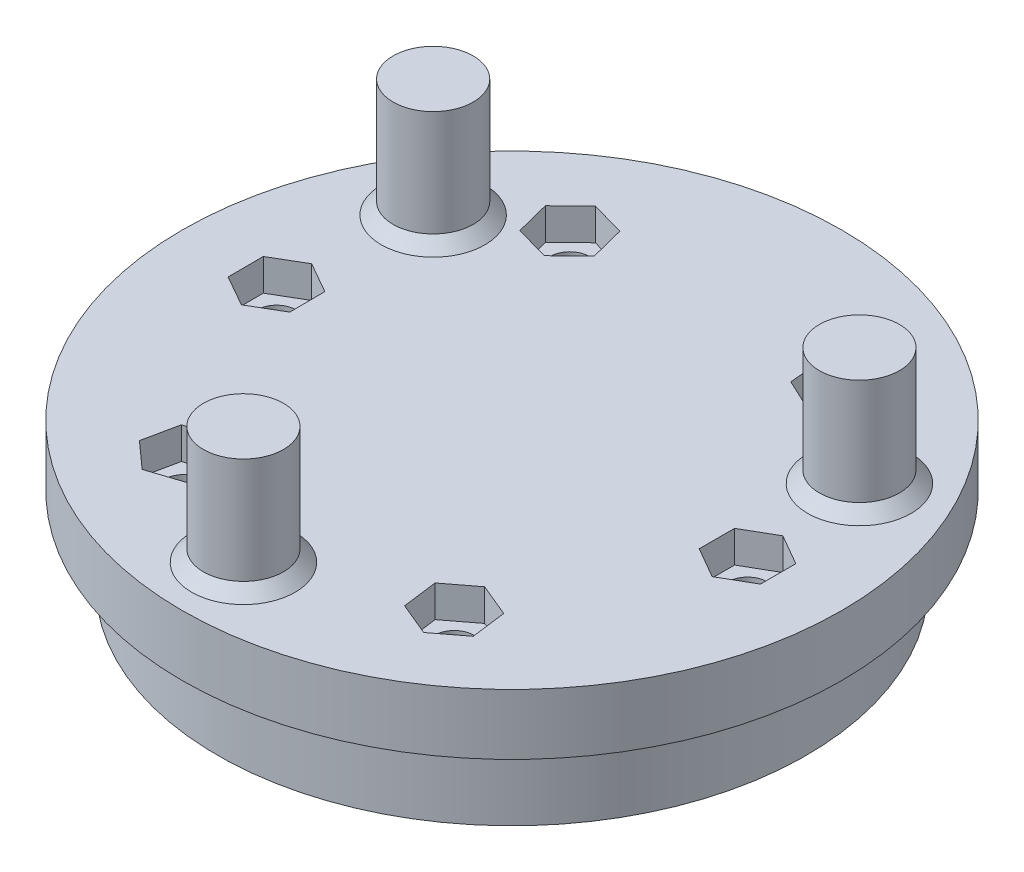
SolidWorks part; units mm, degrees
ref_plane "Front Plane" through (0, 0, 0) normal (0, 0, 1) x (1, 0, 0)
ref_plane "Top Plane" through (0, 0, 0) normal (0, 1, 0) x (1, 0, 0)
ref_plane "Right Plane" through (0, 0, 0) normal (1, 0, 0) x (0, 0, -1)
sketch "Sketch3" plane through (0, 0, 0) normal (0, 1, 0) x (1, 0, 0)
  circle A0 centre (0, 0) radius 28
  dimension "D1" = 56
extrude "Boss-Extrude1" add sketch "Sketch3" along normal blind 5.15
sketch "Sketch6" plane through (0, 0, 0) normal (0, -1, 0) x (1, 0, 0)
  circle A0 centre (0, 0) radius 25
  dimension "D1" = 50
extrude "Boss-Extrude4" add sketch "Sketch6" along normal blind 7
sketch "Sketch7" plane through (0, 5.15, 0) normal (0, 1, 0) x (1, 0, 0)
  line L0 (0, 0) -> (28, 0) construction
  line L1 (0, 0) -> (-17.3949, 11.0818) construction
  line L2 (0, 0) -> (-0.9542, -21.8542) construction
  line L3 (0, 0) -> (24.8363, 12.929) construction
  circle A0 centre (0, 0) radius 28 construction
  circle A8 centre (-0.9542, -21.8542) radius 3.4
  circle A9 centre (-18.4492, 11.7534) radius 3.4
  circle A10 centre (19.4034, 10.1008) radius 3.4
  point P17 (0, 0)
  dimension "D4" = 3
  dimension "D7" = 27.5
  dimension "D3" = 6.8
  dimension "D2" = 120
  dimension "D1" = 120
extrude "Boss-Extrude5" add sketch "Sketch7" along normal blind 10
sketch "Sketch8" plane through (0, 0, 0) normal (0, -1, 0) x (1, 0, 0)
  line L0 (0, 0) -> (20, 0) construction
  line L1 (0, 25) -> (0, -25) construction
  line L2 (0, 0) -> (11.4715, 16.383) construction
  line L3 (0, 0) -> (11.4715, -16.383) construction
  line L4 (0, 0) -> (-13.6508, -19.4954) construction
  line L5 (0, 0) -> (-20, 0) construction
  line L6 (0, 0) -> (-11.4715, -16.383) construction
  line L7 (0, 0) -> (-11.4715, 16.383) construction
  circle A0 centre (20, 0) radius 1.65
  circle A1 centre (0, 0) radius 25 construction
  circle A2 centre (0, 0) radius 25 construction
  circle A3 centre (-20, 0) radius 1.65
  circle A4 centre (11.4715, 16.383) radius 1.65
  circle A5 centre (-11.4715, -16.383) radius 1.65
  circle A6 centre (11.4715, -16.383) radius 1.65
  circle A7 centre (-11.4715, 16.383) radius 1.65
  dimension "D1" = 55
  dimension "D2" = 55
  dimension "D3" = 35
  dimension "D4" = 55
  dimension "D5" = 35
extrude "Cut-Extrude1" cut sketch "Sketch8" against normal through all and the other way blind 10
sketch "Sketch11" plane through (0, 5.15, 0) normal (0, 1, 0) x (1, 0, 0)
  line L1 (11.8581, -19.3603) -> (14.2432, -17.5369)
  line L2 (14.2432, -17.5369) -> (13.8566, -14.5597)
  line L3 (13.8566, -14.5597) -> (11.085, -13.4058)
  line L4 (11.085, -13.4058) -> (8.6999, -15.2292)
  line L5 (8.6999, -15.2292) -> (9.0865, -18.2064)
  line L6 (9.0865, -18.2064) -> (11.8581, -19.3603)
  line L7 (-12.0914, -19.3206) -> (-9.2375, -18.3886)
  line L8 (-9.2375, -18.3886) -> (-8.6176, -15.4511)
  line L9 (-8.6176, -15.4511) -> (-10.8516, -13.4455)
  line L10 (-10.8516, -13.4455) -> (-13.7056, -14.3774)
  line L11 (-13.7056, -14.3774) -> (-14.3254, -17.315)
  line L12 (-14.3254, -17.315) -> (-12.0914, -19.3206)
  line L13 (-22.5906, -1.5173) -> (-19.9813, -3.0022)
  line L14 (-19.9813, -3.0022) -> (-17.3907, -1.4849)
  line L15 (-17.3907, -1.4849) -> (-17.4094, 1.5173)
  line L16 (-17.4094, 1.5173) -> (-20.0187, 3.0022)
  line L17 (-20.0187, 3.0022) -> (-22.6093, 1.4849)
  line L18 (-22.6093, 1.4849) -> (-22.5906, -1.5173)
  line L19 (20, -3.0022) -> (22.6, -1.5011)
  line L20 (22.6, -1.5011) -> (22.6, 1.5011)
  line L21 (22.6, 1.5011) -> (20, 3.0022)
  line L22 (20, 3.0022) -> (17.4, 1.5011)
  line L23 (17.4, 1.5011) -> (17.4, -1.5011)
  line L24 (17.4, -1.5011) -> (20, -3.0022)
  line L25 (9.0083, 14.6668) -> (11.7262, 13.3916)
  line L26 (11.7262, 13.3916) -> (14.1895, 15.1079)
  line L27 (14.1895, 15.1079) -> (13.9348, 18.0993)
  line L28 (13.9348, 18.0993) -> (11.2168, 19.3744)
  line L29 (11.2168, 19.3744) -> (8.7536, 17.6582)
  line L30 (8.7536, 17.6582) -> (9.0083, 14.6668)
  line L31 (-10.7297, 13.4739) -> (-8.5812, 15.5709)
  line L32 (-8.5812, 15.5709) -> (-9.3231, 18.48)
  line L33 (-9.3231, 18.48) -> (-12.2134, 19.2922)
  line L34 (-12.2134, 19.2922) -> (-14.3618, 17.1952)
  line L35 (-14.3618, 17.1952) -> (-13.62, 14.286)
  line L36 (-13.62, 14.286) -> (-10.7297, 13.4739)
  circle A0 centre (11.4715, -16.383) radius 2.6 construction
  circle A1 centre (-11.4715, -16.383) radius 2.6 construction
  circle A2 centre (-20, 0) radius 2.6 construction
  circle A3 centre (20, 0) radius 2.6 construction
  circle A4 centre (11.4715, 16.383) radius 2.6 construction
  circle A5 centre (-11.4715, 16.383) radius 2.6 construction
  dimension "D1" = 5.2
extrude "Cut-Extrude3" cut sketch "Sketch11" against normal blind 2.7
chamfer "Chamfer1" distance 1 angle 45 3 edges at (19.4034, 5.15, -6.7008) (-18.4492, 5.15, -8.3534) (-0.9542, 5.15, 25.2542)
